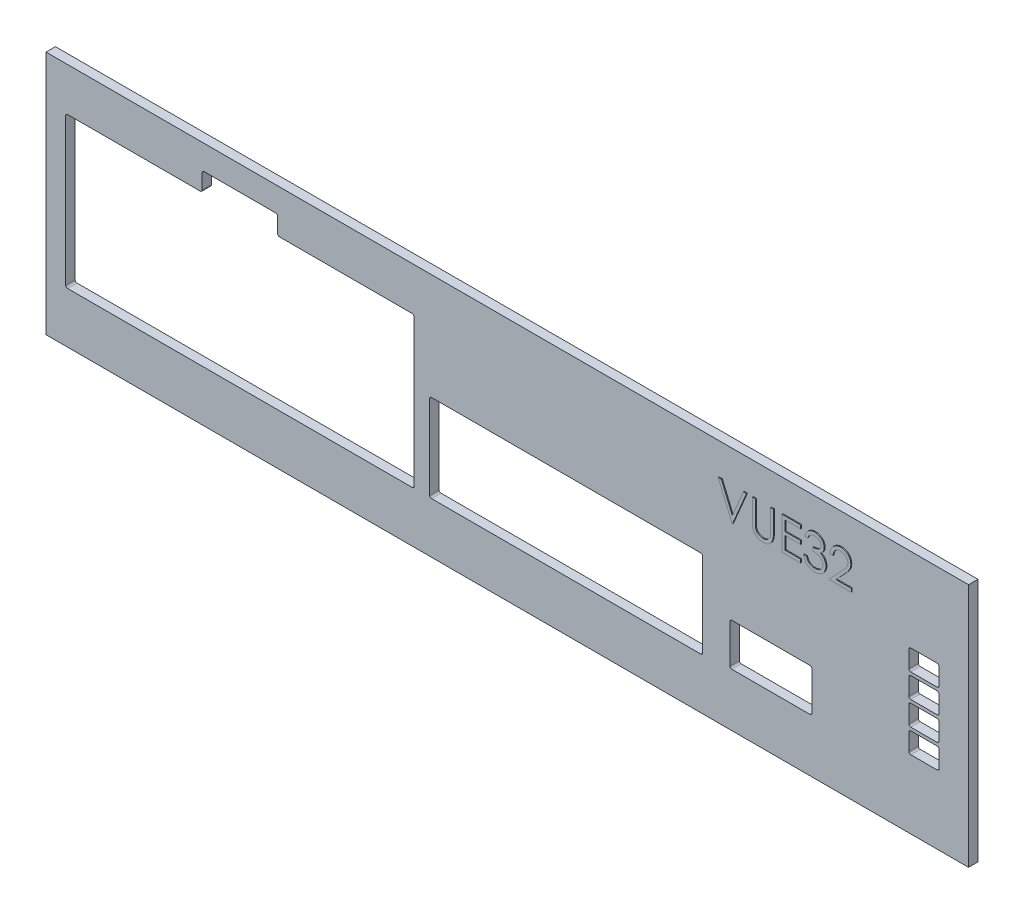
SolidWorks part; units mm, degrees
material "6061-T6 (SS)"
ref_plane "Plan de face" through (0, 0, 0) normal (0, 0, 1) x (1, 0, 0)
ref_plane "Plan de dessus" through (0, 0, 0) normal (0, 1, 0) x (1, 0, 0)
ref_plane "Plan de droite" through (0, 0, 0) normal (1, 0, 0) x (0, 0, -1)
sketch "Esquisse1" plane through (0, 0, 0) normal (0, 0, 1) x (1, 0, 0)
  line L1 (-49, 13) -> (49, 13)
  line L2 (-49, 13) -> (-49, -13)
  line L3 (-49, -13) -> (49, -13)
  line L4 (49, 13) -> (49, -13)
  point P4 (0, 13)
  point P7 (-49, 0)
  dimension "D1" = 98
  dimension "D2" = 26
extrude "Boss.-Extru.1" add sketch "Esquisse1" along normal blind 1
sketch "Esquisse2" plane through (0, 0, 1) normal (0, 0, 1) x (1, 0, 0)
  line L0 (-49, 13) -> (-49, -13) construction
  line L1 (-46.9074, 8.4) -> (-32.4074, 8.4)
  line L2 (-46.9074, 8.4) -> (-46.9074, -7.6)
  line L3 (-46.9074, -7.6) -> (-9.9074, -7.6)
  line L4 (-9.9074, 8.4) -> (-9.9074, -7.6)
  line L5 (-8.25, 1.7) -> (20.75, 1.7)
  line L6 (-8.25, 1.7) -> (-8.25, -7.6)
  line L7 (-8.25, -7.6) -> (20.75, -7.6)
  line L8 (20.75, 1.7) -> (20.75, -7.6)
  line L9 (23.65, -2.85) -> (32.35, -2.85)
  line L10 (23.65, -2.85) -> (23.65, -7.35)
  line L11 (23.65, -7.35) -> (32.35, -7.35)
  line L12 (32.35, -2.85) -> (32.35, -7.35)
  line L13 (44.256, 3.6051) -> (44.256, -6.0149) construction
  line L14 (45.756, 3.6051) -> (42.756, 3.6051) construction
  line L15 (42.756, -6.0149) -> (45.756, -6.0149) construction
  line L17 (23.65, -7.35) -> (32.35, -2.85) construction
  line L18 (42.656, 1.91) -> (45.856, 1.91)
  line L19 (22.5, -9.6) -> (33.5, -9.6) construction
  line L20 (22.5, -9.6) -> (22.5, -0.6) construction
  line L21 (22.5, -0.6) -> (33.5, -0.6) construction
  line L22 (33.5, -9.6) -> (33.5, -0.6) construction
  line L23 (22.5, -9.6) -> (33.5, -0.6) construction
  line L24 (22.5, -0.6) -> (33.5, -9.6) construction
  line L25 (42.656, 1.91) -> (42.656, 4.11)
  line L26 (42.656, 4.11) -> (45.856, 4.11)
  line L27 (45.856, 1.91) -> (45.856, 4.11)
  line L28 (42.656, 1.91) -> (45.856, 4.11) construction
  line L29 (42.656, 4.11) -> (45.856, 1.91) construction
  line L30 (42.656, -0.63) -> (45.856, -0.63)
  line L31 (42.656, -0.63) -> (42.656, 1.57)
  line L32 (-49, -13) -> (49, -13) construction
  line L33 (42.656, 1.57) -> (45.856, 1.57)
  line L34 (-24.4074, 8.4) -> (-9.9074, 8.4)
  line L35 (49, 13) -> (-49, 13) construction
  line L36 (-32.4074, 8.4) -> (-32.4074, 10.4)
  line L37 (-32.4074, 10.4) -> (-24.4074, 10.4)
  line L38 (-24.4074, 8.4) -> (-24.4074, 10.4)
  line L39 (45.856, -0.63) -> (45.856, 1.57)
  line L40 (42.656, -0.63) -> (45.856, 1.57) construction
  line L41 (42.656, 1.57) -> (45.856, -0.63) construction
  line L42 (42.656, -3.17) -> (45.856, -3.17)
  line L43 (42.656, -3.17) -> (42.656, -0.97)
  line L44 (42.656, -0.97) -> (45.856, -0.97)
  line L45 (45.856, -3.17) -> (45.856, -0.97)
  line L46 (42.656, -3.17) -> (45.856, -0.97) construction
  line L47 (42.656, -0.97) -> (45.856, -3.17) construction
  line L48 (42.656, -5.71) -> (45.856, -5.71)
  line L49 (42.656, -5.71) -> (42.656, -3.51)
  line L50 (42.656, -3.51) -> (45.856, -3.51)
  line L51 (45.856, -5.71) -> (45.856, -3.51)
  line L52 (42.656, -5.71) -> (45.856, -3.51) construction
  line L53 (42.656, -3.51) -> (45.856, -5.71) construction
  point P18 (44.256, 3.01)
  point P25 (-49, 0)
  point P26 (28, -5.1)
  point P27 (28, -5.1)
  point P33 (44.256, 0.47)
  point P38 (44.256, -2.07)
  point P43 (-28.4074, 8)
  point P48 (-28.4074, 10.4)
  point P49 (0, 13)
  point P50 (6.25, 1.7)
  point P53 (28, -2.85)
  point P56 (44.256, -4.61)
  dimension "D10" = 3.2
  dimension "D11" = 2.2
  dimension "D12" = 2.54
  dimension "D1" = 37
  dimension "D2" = 16
  dimension "D3" = 6.25
  dimension "D4" = 29
  dimension "D5" = 28
  dimension "D6" = 8.7
  dimension "D7" = 4.5
  dimension "D8" = 11
  dimension "D9" = 9
  dimension "D13" = 2.54
  dimension "D14" = 2.54
  dimension "D15" = 7.29
  dimension "D16" = 5.4
  dimension "D20" = 3.4
  dimension "D24" = 9.3
  dimension "D25" = 2
  dimension "D26" = 8
  dimension "D27" = 0.25
  dimension "D28" = 28.4074
extrude "Enlèv. mat.-Extru.1" cut sketch "Esquisse2" against normal through all
sketch "Esquisse3" plane through (0, 0, 1) normal (0, 0, 1) x (1, 0, 0)
  text T0 "VUE32"
fillet "Congé1" radius 0.2 32 edges at (42.656, -5.71, 0.5) (42.656, -3.17, 0.5) (42.656, -0.63, 0.5) (42.656, 1.91, 0.5) (42.656, -3.51, 0.5) (42.656, -0.97, 0.5) (42.656, 1.57, 0.5) (42.656, 4.11, 0.5) (45.856, 4.11, 0.5) (45.856, 1.57, 0.5) (45.856, -0.97, 0.5) (45.856, -3.51, 0.5) (45.856, 1.91, 0.5) (45.856, -0.63, 0.5) (45.856, -3.17, 0.5) (45.856, -5.71, 0.5) (32.35, -7.35, 0.5) (23.65, -7.35, 0.5) (23.65, -2.85, 0.5) (32.35, -2.85, 0.5) (20.75, 1.7, 0.5) (20.75, -7.6, 0.5) (-8.25, 1.7, 0.5) (-8.25, -7.6, 0.5) (-46.9074, -7.6, 0.5) (-9.9074, -7.6, 0.5) (-9.9074, 8.4, 0.5) (-24.4074, 10.4, 0.5) (-24.4074, 8.4, 0.5) (-32.4074, 10.4, 0.5) (-32.4074, 8.4, 0.5) (-46.9074, 8.4, 0.5)
extrude "Boss.-Extru.2" add sketch "Esquisse3" along normal blind 0.1
